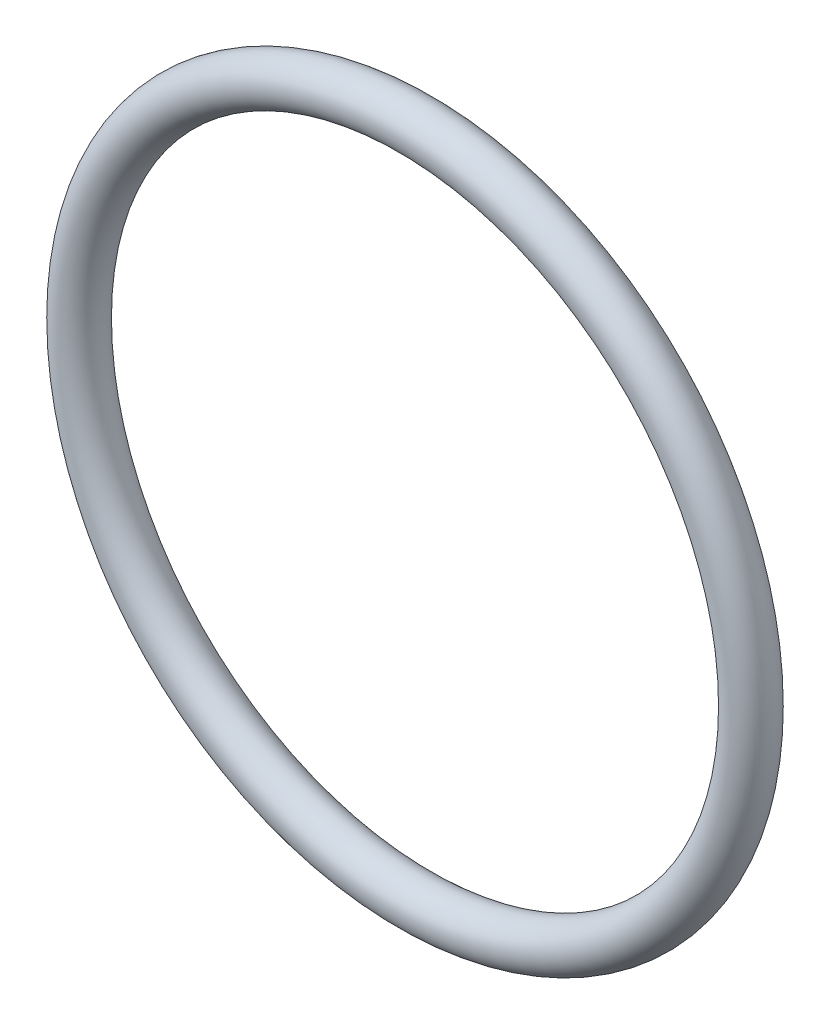
SolidWorks part; units mm, degrees
material "Амортизационная резина"
ref_plane "Спереди" through (0, 0, 0) normal (0, 0, 1) x (1, 0, 0)
ref_plane "Сверху" through (0, 0, 0) normal (0, 1, 0) x (1, 0, 0)
ref_plane "Справа" through (0, 0, 0) normal (1, 0, 0) x (0, 0, -1)
sketch "Sketch1" plane through (0, 0, 0) normal (0, 0, 1) x (1, 0, 0)
  line L0 (0, 20.5) -> (0, -20.5) construction
  circle A0 centre (0, 0) radius 20.5
  dimension "D1" = 41
sketch "Sketch2" plane through (0, 0, 0) normal (1, 0, 0) x (0, 0, -1)
  line L0 (0, 0) -> (5.7855, 0) construction
  line L1 (0, 0) -> (-5.7855, 0) construction
  circle A0 centre (0, 22) radius 1.5
  point P6 (30.9025, 0)
  point P7 (44.547, 0)
  point P9 (0, 0)
  point P11 (42.8902, 0)
  point P12 (-11.4977, 0)
  point P13 (0, 0)
  point P14 (-5.7855, 0)
  dimension "D1" = 3
revolve "Revolve1" add sketch "Sketch2" angle 360 about L1
equation "\"d1\"=44"
equation "\"сечение\"=3"
equation "\"диаметр уплотнителя\"=44"
